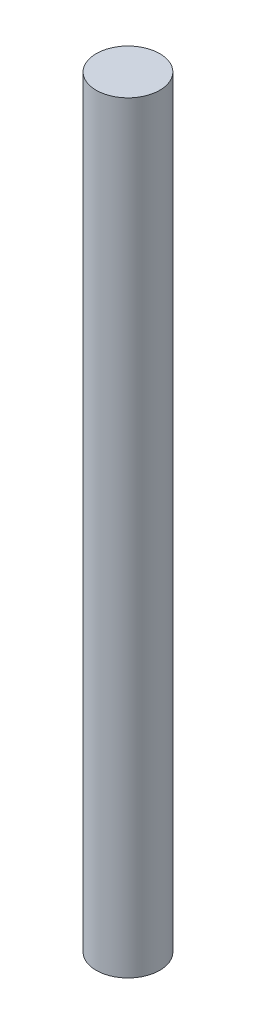
SolidWorks part; units mm, degrees
material "Commercially Pure CP-Ti UNS R50400 (SS)"
ref_plane "Front Plane" through (0, 0, 0) normal (0, 0, 1) x (1, 0, 0)
ref_plane "Top Plane" through (0, 0, 0) normal (0, 1, 0) x (1, 0, 0)
ref_plane "Right Plane" through (0, 0, 0) normal (1, 0, 0) x (0, 0, -1)
sketch "Sketch1" plane through (0, 0, 0) normal (0, 1, 0) x (1, 0, 0)
  circle A0 centre (0, 0) radius 1.5875
  dimension "D1" = 3.175
extrude "Boss-Extrude1" add sketch "Sketch1" along normal blind 38.1
